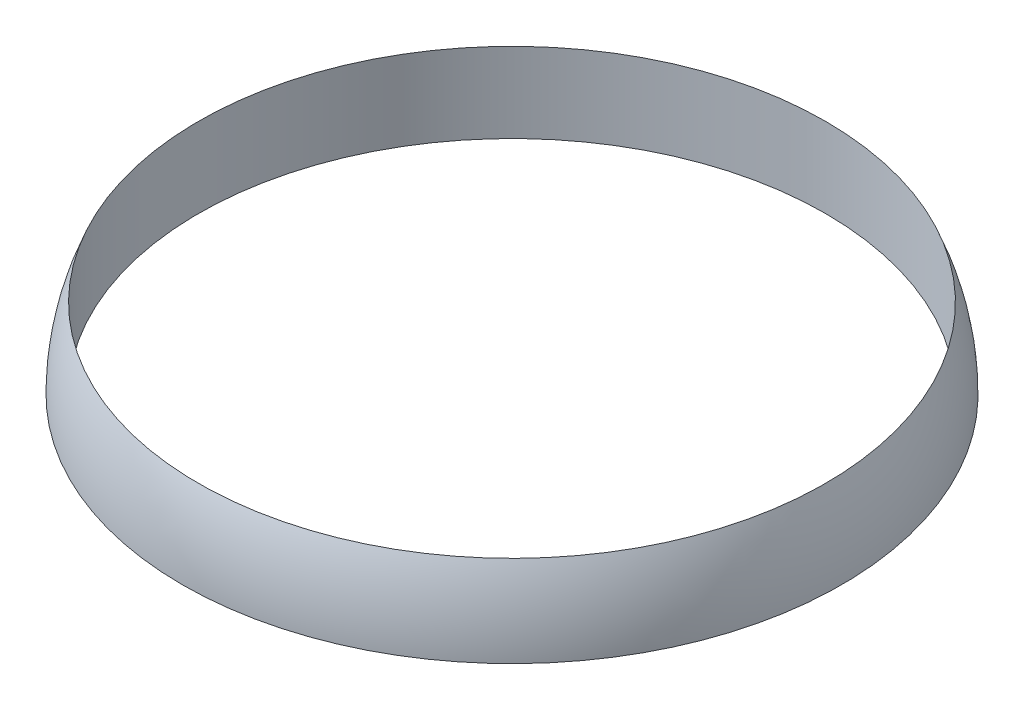
SolidWorks part; units mm, degrees
material "CFRP Filament"
ref_plane "Front Plane" through (0, 0, 0) normal (0, 0, 1) x (1, 0, 0)
ref_plane "Top Plane" through (0, 0, 0) normal (0, 1, 0) x (1, 0, 0)
ref_plane "Right Plane" through (0, 0, 0) normal (1, 0, 0) x (0, 0, -1)
sketch "Sketch1" plane through (0, 0, 0) normal (1, 0, 0) x (0, 0, -1)
  line L0 (78.5, 0) -> (78.5, 20)
  line L1 (78.5, 0) -> (82.5, 0)
  line L2 (0, 0) -> (0, 45.7169) construction
  arc A1 (82.5, 0) -> (78.5, 20) centre (30.5, 0) ccw
  dimension "D1" = 4
  dimension "D2" = 20
  dimension "D3" = 78.5
revolve "Revolve1" add sketch "Sketch1" angle 360 about L2
